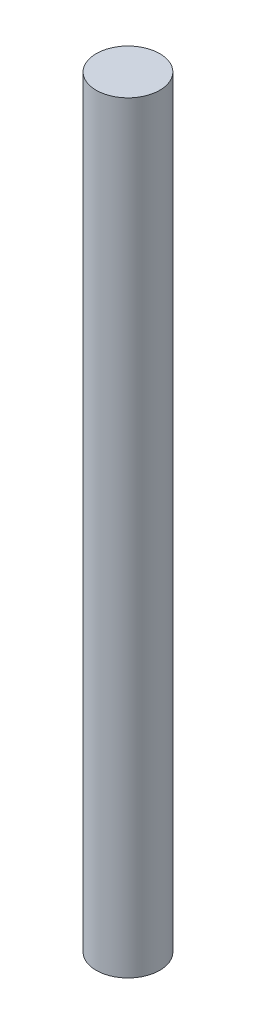
SolidWorks part; units mm, degrees
material "Brass"
ref_plane "Front Plane" through (0, 0, 0) normal (0, 0, 1) x (1, 0, 0)
ref_plane "Top Plane" through (0, 0, 0) normal (0, 1, 0) x (1, 0, 0)
ref_plane "Right Plane" through (0, 0, 0) normal (1, 0, 0) x (0, 0, -1)
sketch "Sketch1" plane through (0, 0, 0) normal (0, 1, 0) x (1, 0, 0)
  circle A0 centre (0, 0) radius 1
  dimension "D1" = 2
extrude "Boss-Extrude1" add sketch "Sketch1" along normal blind 24
equation "\"Pin_Length\"= 24"
equation "\"D1@Boss-Extrude1\"= \"Pin_Length\""
